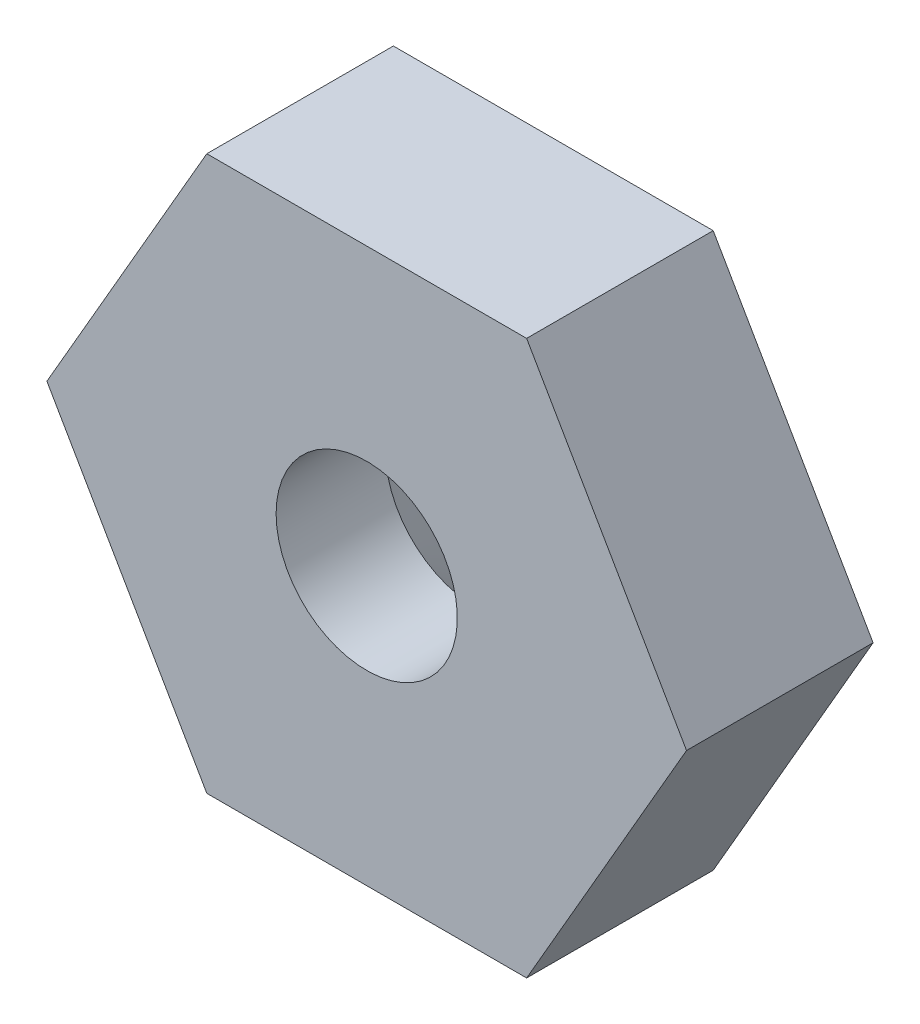
SolidWorks part; units mm, degrees
ref_plane "Front Plane" through (0, 0, 0) normal (0, 0, 1) x (1, 0, 0)
ref_plane "Top Plane" through (0, 0, 0) normal (0, 1, 0) x (1, 0, 0)
ref_plane "Right Plane" through (0, 0, 0) normal (1, 0, 0) x (0, 0, -1)
sketch "Sketch1" plane through (0, 0, 0) normal (0, 0, 1) x (1, 0, 0)
  line L1 (3, -5.1962) -> (6, 0)
  line L2 (6, 0) -> (3, 5.1962)
  line L3 (3, 5.1962) -> (-3, 5.1962)
  line L4 (-3, 5.1962) -> (-6, 0)
  line L5 (-6, 0) -> (-3, -5.1962)
  line L6 (-3, -5.1962) -> (3, -5.1962)
  circle A0 centre (0, 0) radius 5.1962 construction
  point P1 (0, 5.1962)
  dimension "D1" = 6
extrude "Boss-Extrude1" add sketch "Sketch1" along normal mid plane 3.5
hole_wizard "CSK for M3 Countersunk Flat Head Screw1" positions "Sketch4" profile "Sketch5" countersink size "M3" standard "DIN"
sketch "Sketch4" plane through (0, 0, -1.75) normal (0, 0, -1) x (-1, 0, 0)
  point P0 (0, 0)
sketch "Sketch5" plane through (0, 0, -1.75) normal (1, 0, 0) x (0, 1, 0)
  line L0 (0, 0) -> (0, 4.5215)
  line L1 (0, 4.5215) -> (1.7, 3.5)
  line L2 (1.7, 3.5) -> (1.7, 1.45)
  line L3 (1.7, 1.45) -> (3.15, 0)
  line L5 (3.15, 0) -> (0, 0)
  line L6 (-1.7, 1.45) -> (-3.15, 0) construction
  line L10 (0, 4.5215) -> (-1.7, 3.5) construction
  line L11 (0, -6.35) -> (0, 107.95) construction
  dimension "Hole Dia." = 3.4
  dimension "Hole Depth" = 3.5
  dimension "Near C'Sink Dia." = 6.3
  dimension "Near C'Sink Angle" = 90
  dimension "Drill Angle" = 118
